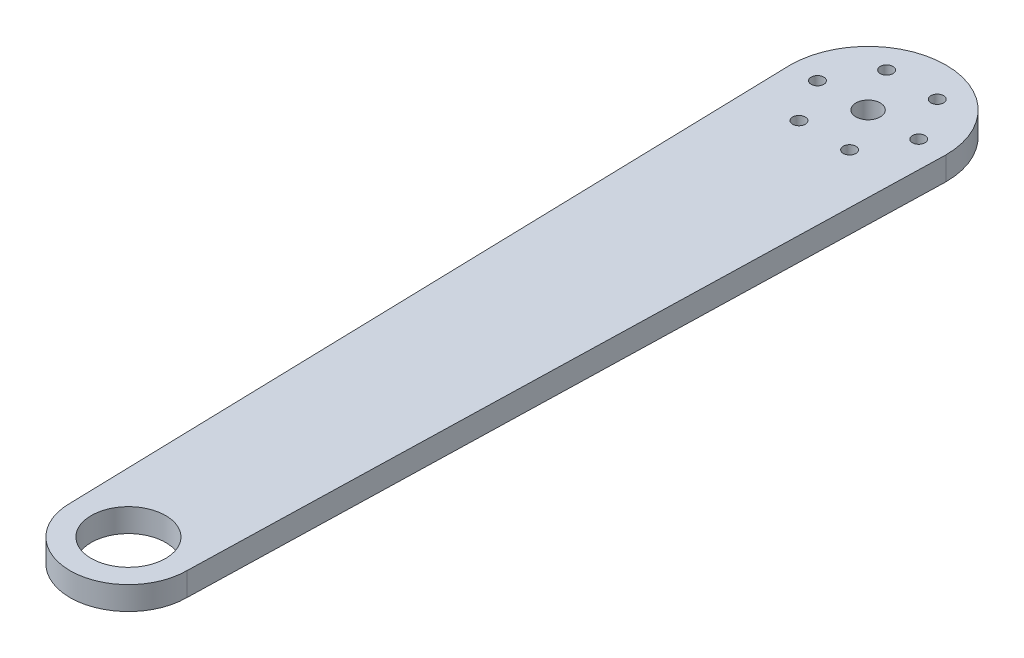
SolidWorks part; units mm, degrees
ref_plane "Front Plane" through (0, 0, 0) normal (0, 0, 1) x (1, 0, 0)
ref_plane "Top Plane" through (0, 0, 0) normal (0, 1, 0) x (1, 0, 0)
ref_plane "Right Plane" through (0, 0, 0) normal (1, 0, 0) x (0, 0, -1)
sketch "Sketch1" plane through (0, 0, 0) normal (0, 1, 0) x (1, 0, 0)
  line L0 (-15, -190) -> (-20, 0)
  line L1 (20, 0) -> (15, -190)
  line L2 (0, -190) -> (0, -117.0566) construction
  circle A0 centre (0, 0) radius 3.125
  circle A1 centre (-13, 0) radius 1.625
  arc A2 (20, 0) -> (-20, 0) centre (0, 0) ccw
  circle A3 centre (-6.5, 11.2583) radius 1.625
  circle A4 centre (6.5, 11.2583) radius 1.625
  circle A5 centre (13, 0) radius 1.625
  circle A6 centre (6.5, -11.2583) radius 1.625
  circle A7 centre (-6.5, -11.2583) radius 1.625
  arc A8 (-15, -190) -> (15, -190) centre (0, -190) ccw
  circle A9 centre (0, -190) radius 9.55
  point P18 (0, 0)
  dimension "D2" = 3.25
  dimension "D3" = 6.25
  dimension "D4" = 40
  dimension "D7" = 30
  dimension "D8" = 19.1
  dimension "D1" = 13
  dimension "D6" = 190
  dimension "D9" = 1.507
  dimension "D5" = 6
extrude "Boss-Extrude1" add sketch "Sketch1" along normal blind 6
